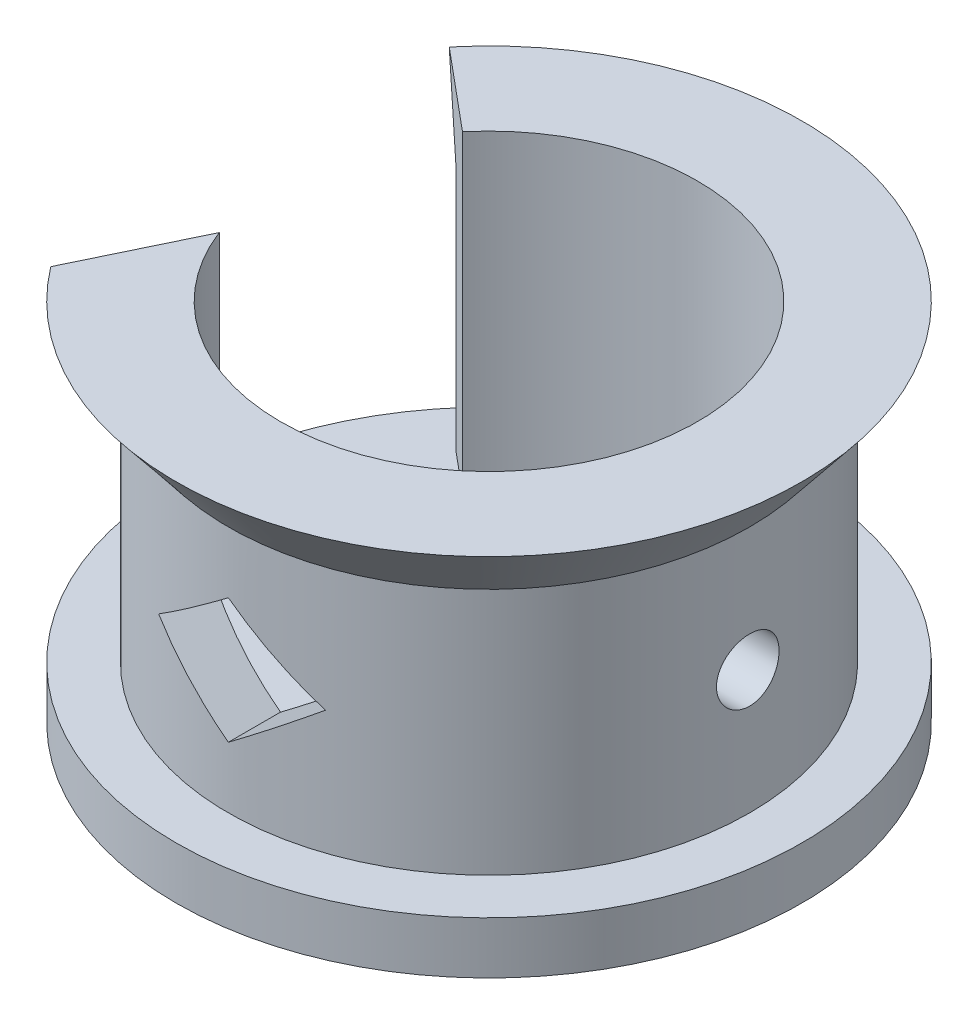
SolidWorks part; units mm, degrees
ref_plane "Front Plane" through (0, 0, 0) normal (0, 0, 1) x (1, 0, 0)
ref_plane "Top Plane" through (0, 0, 0) normal (0, 1, 0) x (1, 0, 0)
ref_plane "Right Plane" through (0, 0, 0) normal (1, 0, 0) x (0, 0, -1)
sketch "Sketch4" plane through (0, 0, 0) normal (0, 1, 0) x (1, 0, 0)
  circle A0 centre (0, 0) radius 6
extrude "Boss-Extrude3" add sketch "Sketch4" along normal blind 1
sketch "Sketch5" plane through (0, 1, 0) normal (0, 1, 0) x (1, 0, 0)
  circle A0 centre (0, 0) radius 5
  circle A1 centre (0, 0) radius 4
extrude "Boss-Extrude4" add sketch "Sketch5" along normal blind 4.75
sketch "Sketch6" plane through (0, 0, 0) normal (0, 0, 1) x (1, 0, 0)
  line L0 (0, 5.75) -> (5, 5.75)
  line L1 (4, 5.75) -> (-4, 5.75) construction
  line L7 (6, 7) -> (5, 5.75)
  line L8 (0, 7) -> (6, 7)
  line L10 (0, 5.75) -> (0, 7)
revolve "Revolve4" add sketch "Sketch6" angle 360 about L10
sketch "Sketch9" plane through (0, 7, 0) normal (0, 1, 0) x (1, 0, 0)
  circle A0 centre (0, 0) radius 4
extrude "Cut-Extrude3" cut sketch "Sketch9" against normal blind 3
sketch "Sketch11" plane through (0, 0, 0) normal (0, 0, 1) x (1, 0, 0)
  line L0 (0, 3.375) -> (0, 4.575)
  line L1 (0, 3.375) -> (0, 2.175)
  line L2 (0, 3.375) -> (-1.2, 3.375)
  line L3 (0, 3.375) -> (1.2, 3.375)
  line L5 (0, 2.175) -> (1.6, 3.375)
  line L6 (0, 4.575) -> (1.6, 3.375)
  line L7 (0, 3.375) -> (-1.6, 3.375)
  line L8 (-1.6, 3.375) -> (0, 4.575)
  line L9 (-1.6, 3.375) -> (0, 2.175)
  line L15 (0, 3.375) -> (1.6, 3.375)
extrude "Cut-Extrude7" cut sketch "Sketch11" along normal blind 10 contours L3 L15 L6 L0 | L8 L7 L2 L0 | L7 L9 L1 L2 | L15 L3 L1 L5
sketch "Sketch12" plane through (0, 0, 0) normal (1, 0, 0) x (0, 0, -1)
  line L0 (0, 5.75) -> (0, 1)
  line L1 (-5, 5.75) -> (5, 5.75) construction
  line L2 (6, 1) -> (-6, 1) construction
  circle A0 centre (0, 3.375) radius 0.6
extrude "Cut-Extrude8" cut sketch "Sketch12" along normal blind 10 contours L0 A0 | L0 A0
sketch "Sketch13" plane through (0, 7, 0) normal (0, 1, 0) x (1, 0, 0)
  line L0 (-3.7299, -1.4449) -> (-1.4944, 3.7104)
  line L1 (-3.7299, -1.4449) -> (-4.7792, -3.6276)
  line L2 (-1.4944, 3.7104) -> (-2.2416, 5.5655)
  line L3 (-4.6068, 3.8441) -> (-3.0712, 2.5627)
  circle A1 centre (0, 0) radius 6 construction
  circle A2 centre (0, 0) radius 4 construction
  circle A3 centre (0, 0) radius 4 construction
  circle A4 centre (0, 0) radius 4
  circle A5 centre (0, 0) radius 6
  circle M3 centre (0, 0) radius 4
  circle M4 centre (0, 0) radius 6
extrude "Cut-Extrude10" cut sketch "Sketch13" against normal blind 6 contours L3 L1 M4 M3
sketch "Sketch14" plane through (0, 1, 0) normal (0, 1, 0) x (1, 0, 0)
  circle A0 centre (0, 0) radius 2.4
extrude "Cut-Extrude11" cut sketch "Sketch14" against normal blind 6
